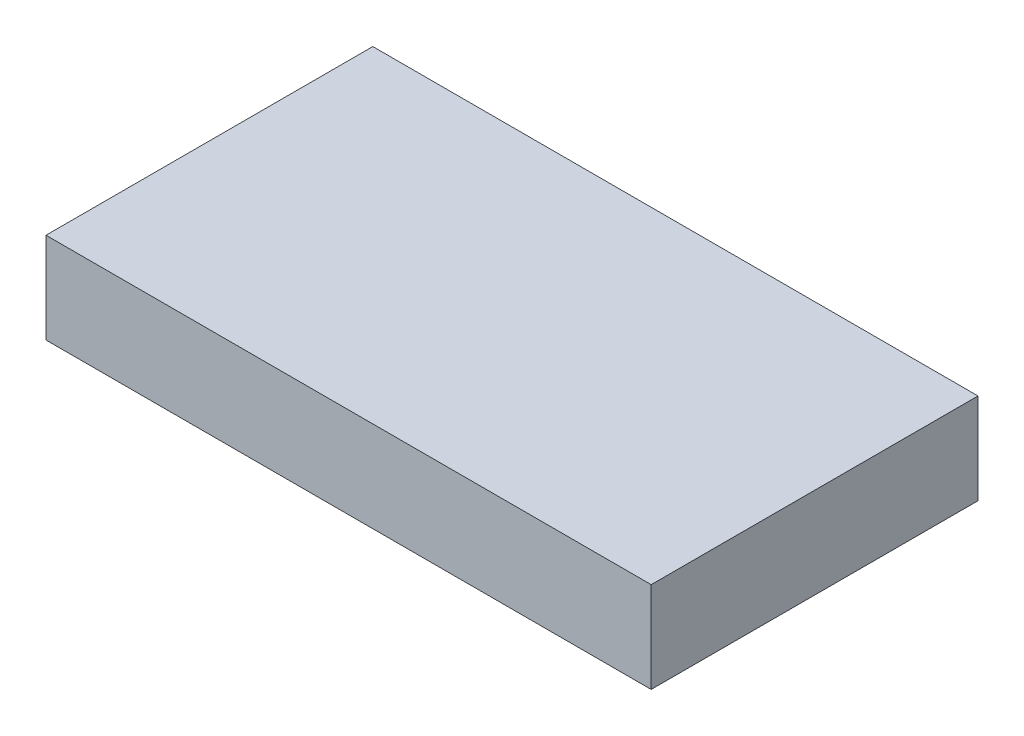
SolidWorks part; units mm, degrees
ref_plane "Front Plane" through (0, 0, 0) normal (0, 0, 1) x (1, 0, 0)
ref_plane "Top Plane" through (0, 0, 0) normal (0, 1, 0) x (1, 0, 0)
ref_plane "Right Plane" through (0, 0, 0) normal (1, 0, 0) x (0, 0, -1)
sketch "Sketch1" plane through (0, 0, 0) normal (0, 1, 0) x (1, 0, 0)
  line L1 (-90.4753, 49.1836) -> (36.5247, 49.1836)
  line L2 (-90.4753, 49.1836) -> (-90.4753, -19.3964)
  line L3 (-90.4753, -19.3964) -> (36.5247, -19.3964)
  line L4 (36.5247, 49.1836) -> (36.5247, -19.3964)
  dimension "D1" = 127
  dimension "D2" = 68.58
extrude "Boss-Extrude1" add sketch "Sketch1" along normal blind 19.05
